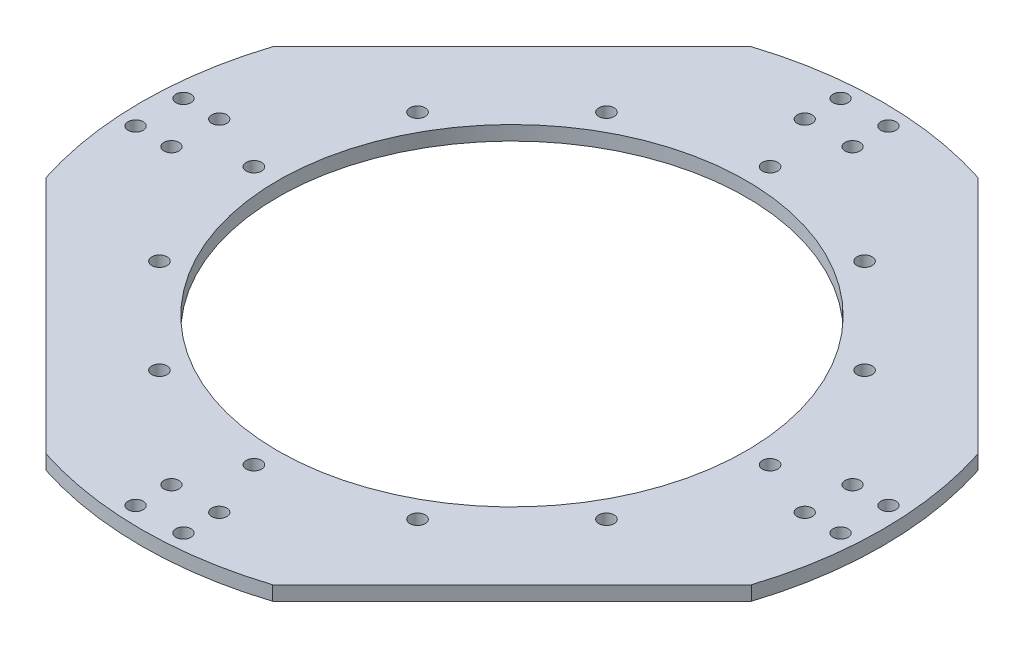
SolidWorks part; units mm, degrees
ref_plane "前视基准面" through (0, 0, 0) normal (0, 0, 1) x (1, 0, 0)
ref_plane "上视基准面" through (0, 0, 0) normal (0, 1, 0) x (1, 0, 0)
ref_plane "右视基准面" through (0, 0, 0) normal (1, 0, 0) x (0, 0, -1)
other "Configuration Table"
sketch "草图1" plane through (0, 0, 0) normal (0, 1, 0) x (1, 0, 0)
  line L1 (0, 54) -> (0, 0) construction
  line L3 (-70, 33.2603) -> (-70, -33.2603) construction
  line L8 (-70, 0) -> (0, 0) construction
  circle A0 centre (0, 0) radius 49
  circle A2 centre (0, 54) radius 1.6
  circle A59 centre (27, 46.7654) radius 1.6
  circle A60 centre (46.7654, 27) radius 1.6
  circle A61 centre (54, 0) radius 1.6
  circle A62 centre (46.7654, -27) radius 1.6
  circle A63 centre (27, -46.7654) radius 1.6
  circle A64 centre (0, -54) radius 1.6
  circle A65 centre (-27, -46.7654) radius 1.6
  circle A66 centre (-46.7654, -27) radius 1.6
  circle A67 centre (-54, 0) radius 1.6
  circle A68 centre (-46.7654, 27) radius 1.6
  circle A69 centre (-27, 46.7654) radius 1.6
  circle A70 centre (-73.75, 5) radius 1.575
  circle A71 centre (-66.25, 5) radius 1.575
  circle A72 centre (-66.25, -5) radius 1.575
  circle A73 centre (-73.75, -5) radius 1.575
  circle A74 centre (5, 73.75) radius 1.575
  circle A75 centre (5, 66.25) radius 1.575
  circle A76 centre (-5, 66.25) radius 1.575
  circle A77 centre (-5, 73.75) radius 1.575
  circle A78 centre (73.75, -5) radius 1.575
  circle A79 centre (66.25, -5) radius 1.575
  circle A80 centre (66.25, 5) radius 1.575
  circle A81 centre (73.75, 5) radius 1.575
  circle A82 centre (-5, -73.75) radius 1.575
  circle A83 centre (-5, -66.25) radius 1.575
  circle A84 centre (5, -66.25) radius 1.575
  circle A85 centre (5, -73.75) radius 1.575
  circle A86 centre (0, 0) radius 77.5
  point P23 (0, 0)
  point P59 (0, 0)
  point P61 (0, 0)
  point P93 (0, 0)
  point P103 (0, 0)
  point P151 (0, 0)
  point P179 (0, 0)
  point P260 (0, 0)
  dimension "D1" = 98
  dimension "D2" = 70
  dimension "D3" = 3.2
  dimension "D6" = 155
  dimension "D8" = 3.15
  dimension "D4" = 54
  dimension "D9" = 3.75
  dimension "D10" = 5
  dimension "D5" = 12
extrude "凸台-拉伸1" add sketch "草图1" along normal blind 3
sketch "草图2" plane through (0, 0, 0) normal (0, -1, 0) x (1, 0, 0)
  line L0 (-10, 87.5) -> (-10, -87.5) construction
  line L1 (77.5, -77.5) -> (-77.5, -77.5) construction
  line L2 (77.5, -77.5) -> (77.5, 77.5) construction
  line L3 (77.5, 77.5) -> (-77.5, 77.5) construction
  line L4 (-77.5, -77.5) -> (-77.5, 77.5) construction
  line L5 (77.5, -77.5) -> (-77.5, 77.5) construction
  line L6 (77.5, 77.5) -> (-77.5, -77.5) construction
  line L7 (-87.5, 10) -> (87.5, 10) construction
  line L8 (10, 87.5) -> (10, -87.5) construction
  line L9 (-87.5, -10) -> (87.5, -10) construction
  line L10 (-10, 87.5) -> (-87.5, 10)
  line L11 (-87.5, 10) -> (-87.5, -10)
  line L12 (-87.5, -10) -> (-10, -87.5)
  line L13 (-10, -87.5) -> (10, -87.5)
  line L14 (10, -87.5) -> (87.5, -10)
  line L15 (87.5, -10) -> (87.5, 10)
  line L16 (87.5, 10) -> (10, 87.5)
  line L17 (10, 87.5) -> (-10, 87.5)
  circle A0 centre (0, 0) radius 77.5 construction
  circle A1 centre (0, 0) radius 77.5
  point P0 (0, 0)
  point P18 (0, 0)
  point P19 (0, 0)
  point P20 (0, 0)
  point P21 (0, 0)
  point P22 (0, 0)
  point P23 (0, 0)
  point P24 (0, 0)
  point P25 (0, 0)
  circle M6 centre (0, 0) radius 77.5
  dimension "D5" = 155
  dimension "D1" = 10
  dimension "D2" = 10
  dimension "D3" = 10
  dimension "D4" = 10
  dimension "D6" = 10
  dimension "D7" = 10
  dimension "D8" = 10
  dimension "D9" = 10
extrude "切除-拉伸1" cut sketch "草图2" against normal blind 10 contours L16 M6 | L14 M6 | L10 M6 | L12 M6
